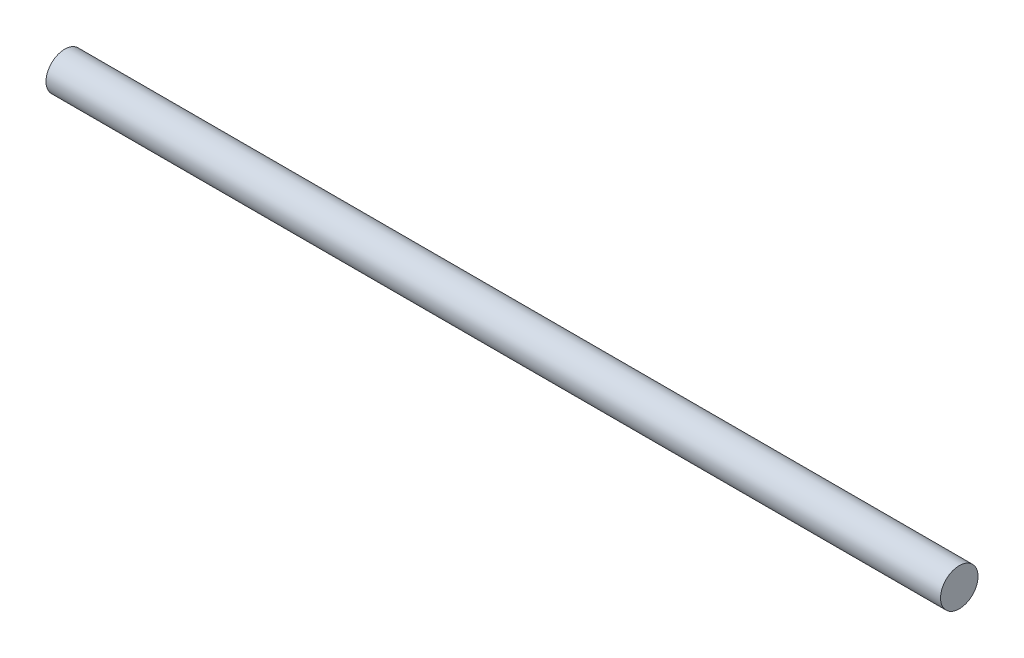
SolidWorks part; units mm, degrees
ref_plane "Front Plane" through (0, 0, 0) normal (1, 0, 0) x (0, 1, 0)
ref_plane "Top Plane" through (0, 0, 0) normal (0, 0, 1) x (0, 1, 0)
ref_plane "Right Plane" through (0, 0, 0) normal (0, 1, 0) x (-1, 0, 0)
sketch "Sketch1" plane through (0, 0, 0) normal (1, 0, 0) x (0, 1, 0)
  circle A0 centre (0, 0) radius 8.89
  dimension "D1" = 17.78
extrude "Boss-Extrude1" add sketch "Sketch1" along normal blind 424.18 contours A0
